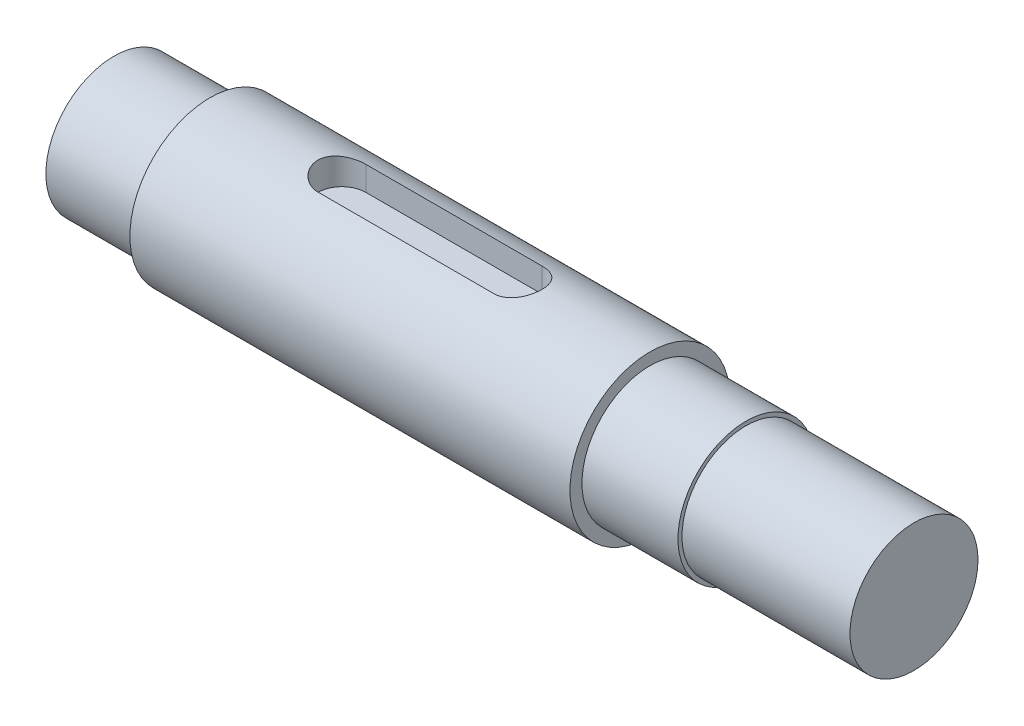
SolidWorks part; units mm, degrees
ref_plane "Спереди" through (0, 0, 0) normal (0, 0, 1) x (1, 0, 0)
ref_plane "Сверху" through (0, 0, 0) normal (0, 1, 0) x (1, 0, 0)
ref_plane "Справа" through (0, 0, 0) normal (1, 0, 0) x (0, 0, -1)
sketch "Эскиз1" plane through (0, 0, 0) normal (0, 0, 1) x (1, 0, 0)
  line L0 (0, 0) -> (0, 8.5)
  line L1 (0, 8.5) -> (12, 8.5)
  line L2 (12, 8.5) -> (12, 10)
  line L3 (12, 10) -> (67, 10)
  line L4 (67, 10) -> (67, 8.5)
  line L5 (67, 8.5) -> (79, 8.5)
  line L6 (79, 8.5) -> (79, 8)
  line L7 (79, 8) -> (100, 8)
  line L8 (100, 8) -> (100, 0)
  line L9 (100, 0) -> (0, 0) construction
  line L10 (0, 0) -> (100, 0)
  dimension "D1" = 17
  dimension "D2" = 20
  dimension "D3" = 17
  dimension "D4" = 16
  dimension "D5" = 12
  dimension "D6" = 55
  dimension "D7" = 21
  dimension "D8" = 100
revolve "Повернуть1" add sketch "Эскиз1" angle 360 about L9
sketch "Эскиз2" plane through (0, 0, 0) normal (0, 1, 0) x (1, 0, 0)
  line L3 (28.5, 0) -> (50.5, 0) construction
  line L6 (28.5, 3) -> (50.5, 3)
  line L7 (28.5, -3) -> (50.5, -3)
  arc A0 (28.5, 3) -> (28.5, -3) centre (28.5, 0) ccw
  arc A1 (50.5, -3) -> (50.5, 3) centre (50.5, 0) ccw
  point P9 (39.5, 0)
extrude "Вырез-Вытянуть1" cut sketch "Эскиз2" along normal through all from offset 6.5
